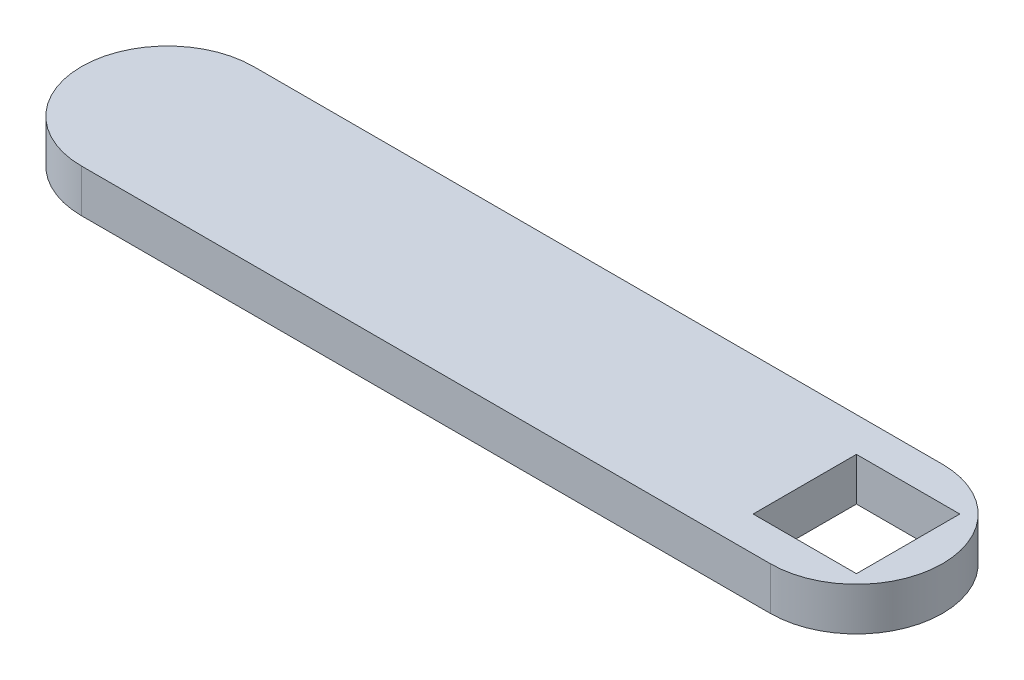
SolidWorks part; units mm, degrees
ref_plane "前视基准面" through (0, 0, 0) normal (0, 0, 1) x (1, 0, 0)
ref_plane "上视基准面" through (0, 0, 0) normal (0, 1, 0) x (1, 0, 0)
ref_plane "右视基准面" through (0, 0, 0) normal (1, 0, 0) x (0, 0, -1)
other "Configuration Table"
sketch "草图1" plane through (0, 0, 0) normal (0, 1, 0) x (1, 0, 0)
  line L0 (0, 0) -> (400, 0) construction
  line L1 (0, 50) -> (400, 50)
  line L2 (0, -50) -> (400, -50)
  arc A0 (0, 50) -> (0, -50) centre (0, 0) ccw
  arc A1 (400, -50) -> (400, 50) centre (400, 0) ccw
  point P3 (200, 0)
  dimension "D1" = 50
  dimension "D2" = 400
extrude "凸台-拉伸1" add sketch "草图1" along normal blind 25
sketch "草图2" plane through (0, 25, 0) normal (0, 1, 0) x (1, 0, 0)
  line L1 (370, -30) -> (430, -30)
  line L2 (370, -30) -> (370, 30)
  line L3 (370, 30) -> (430, 30)
  line L4 (430, -30) -> (430, 30)
  line L5 (370, -30) -> (430, 30) construction
  line L6 (370, 30) -> (430, -30) construction
  point P0 (400, 0)
  dimension "D1" = 60
  dimension "D2" = 60
extrude "切除-拉伸1" cut sketch "草图2" against normal blind 25
